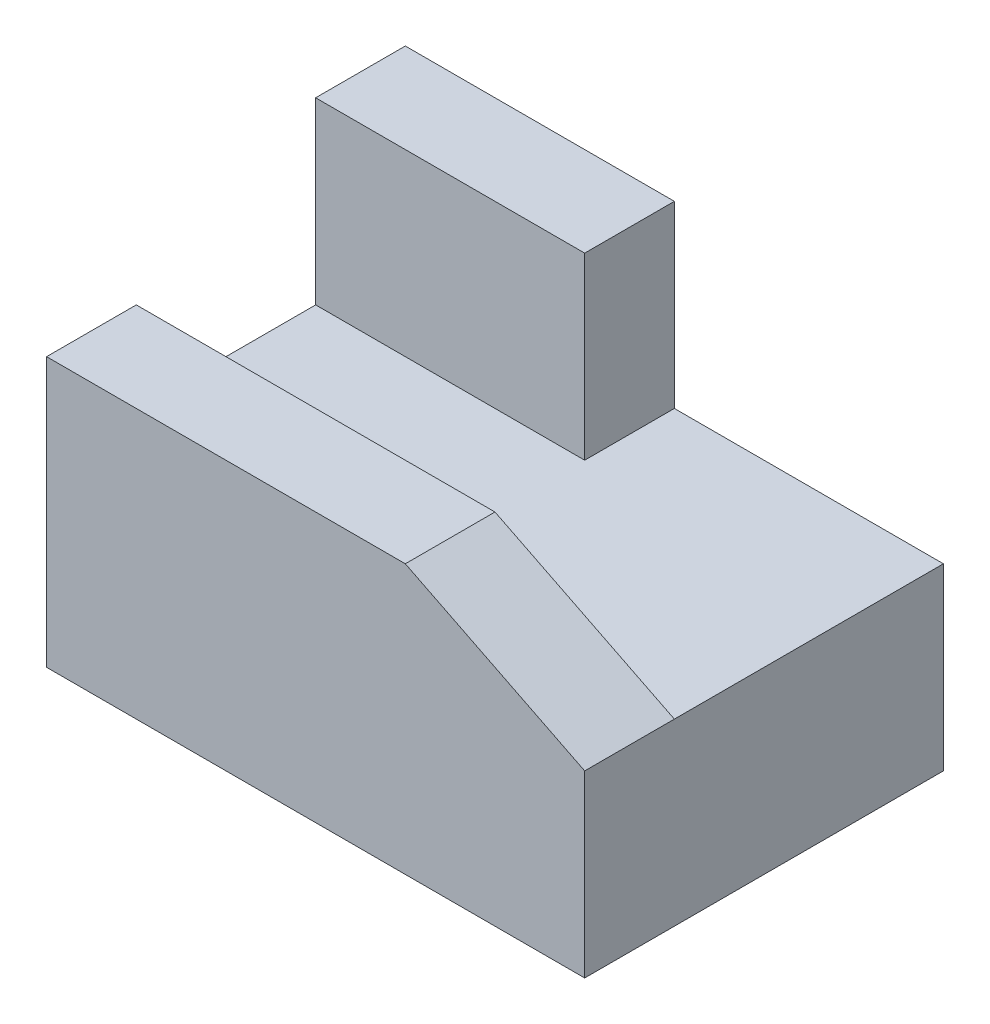
SolidWorks part; units mm, degrees
ref_plane "前基準面" through (0, 0, 0) normal (0, 0, 1) x (1, 0, 0)
ref_plane "上基準面" through (0, 0, 0) normal (0, 1, 0) x (1, 0, 0)
ref_plane "右基準面" through (0, 0, 0) normal (1, 0, 0) x (0, 0, -1)
sketch "草圖1" plane through (0, 0, 0) normal (0, 0, 1) x (1, 0, 0)
  line L0 (0, 26.7287) -> (0, -18.1187) construction
  line L2 (0, 0) -> (-60, 0)
  line L3 (0, 0) -> (0, -40)
  line L4 (0, -40) -> (-60, -40)
  line L5 (-60, 0) -> (-60, -40)
  dimension "D1" = 60
  dimension "D2" = 40
extrude "填料-伸長1" add sketch "草圖1" along normal blind 40
sketch "草圖2" plane through (0, 0, 40) normal (0, 0, 1) x (1, 0, 0)
  line L0 (-30, 0) -> (-30, -10)
  line L1 (0, 0) -> (-60, 0) construction
  line L2 (-30, -10) -> (-20, -10)
  line L3 (-20, -10) -> (0, -20)
  line L4 (0, -40) -> (0, 0) construction
  line L5 (-60, -40) -> (0, -40) construction
  dimension "D1" = 10
  dimension "D2" = 30
  dimension "D3" = 20
  dimension "D4" = 10
extrude "除料-伸長1" cut sketch "草圖2" against normal through all and the other way through all
sketch "草圖4" plane through (0, 0, 0) normal (0, 1, 0) x (1, 0, 0)
  line L0 (-30, 0) -> (-30, -10)
  line L1 (-30, -40) -> (-30, 0) construction
  line L2 (-30, -10) -> (-60, -10)
  line L3 (-60, -40) -> (-60, 0) construction
  line L4 (-60, -10) -> (-60, -30)
  line L5 (-60, -30) -> (0, -30)
  line L6 (0, -40) -> (0, 0) construction
  line L7 (0, -30) -> (0, 0)
  line L8 (0, 0) -> (-30, 0)
  line L9 (-30, -40) -> (-60, -40) construction
  line L10 (-30, 0) -> (-60, 0) construction
  dimension "D1" = 10
  dimension "D2" = 10
extrude "除料-伸長2" cut sketch "草圖4" against normal blind 20
sketch "草圖5" plane through (-30, 0, 0) normal (1, 0, 0) x (0, 0, -1)
  line L4 (-30, -10) -> (-30, 0)
  line L5 (-30, 0) -> (-40, 0)
  line L6 (-40, 0) -> (-40, -10)
  line L7 (-40, -10) -> (-30, -10)
  line L8 (-30, -10) -> (-30, 0)
  line L9 (-30, 0) -> (-40, 0)
  line L10 (-40, 0) -> (-40, -10)
  line L11 (-40, -10) -> (-30, -10)
  dimension "D1" = 0
extrude "除料-伸長3" cut sketch "草圖5" against normal blind 45
